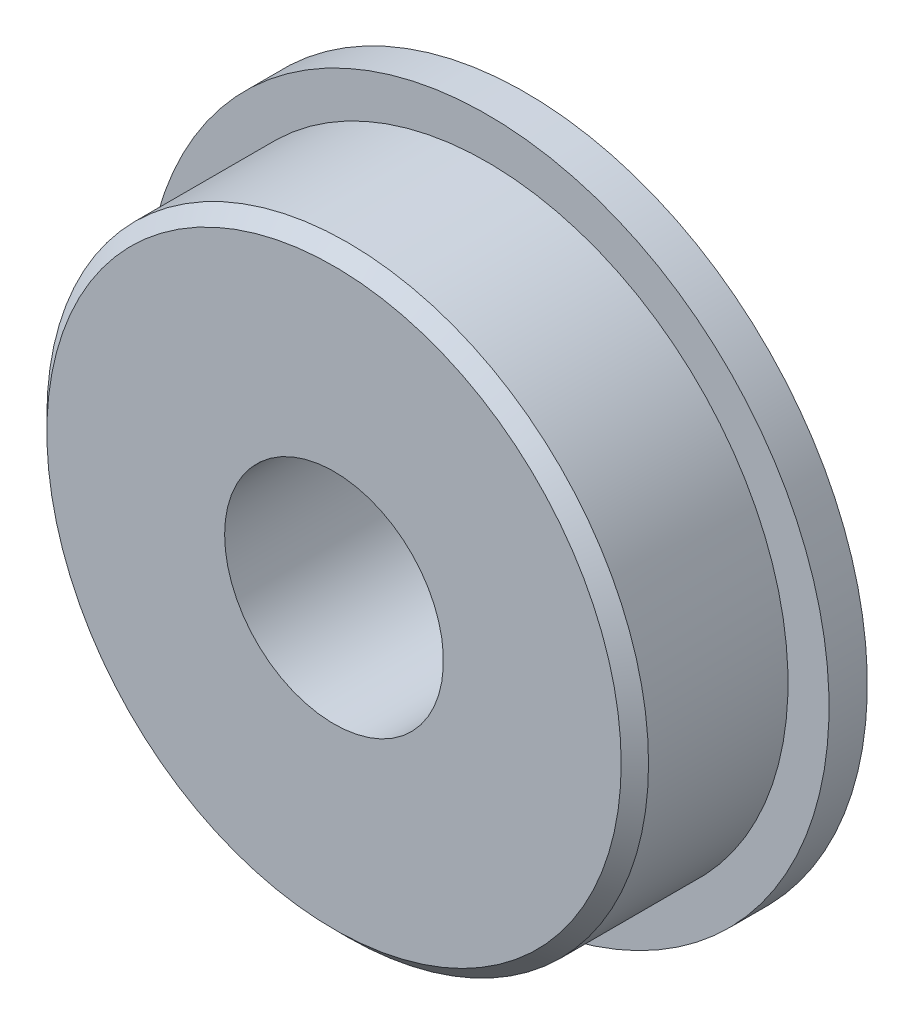
SolidWorks part; units mm, degrees
ref_plane "Front Plane" through (0, 0, 0) normal (0, 0, 1) x (1, 0, 0)
ref_plane "Top Plane" through (0, 0, 0) normal (0, 1, 0) x (1, 0, 0)
ref_plane "Right Plane" through (0, 0, 0) normal (1, 0, 0) x (0, 0, -1)
sketch "Sketch1" plane through (0, 0, 0) normal (0, 1, 0) x (1, 0, 0)
  line L0 (0, 20.1786) -> (0, -22.4643) construction
  line L1 (-16.9286, 0) -> (20.5, 0) construction
  line L2 (-12.5, 0) -> (-12.5, -1.4)
  line L3 (-12.5, -1.4) -> (-11, -1.4)
  line L4 (-11, -1.4) -> (-11, -7)
  line L5 (-11, -7) -> (-4, -7)
  line L6 (-4, -7) -> (-4, 0)
  line L7 (-4, 0) -> (-12.5, 0)
  dimension "D1" = 11
  dimension "D2" = 4
  dimension "D3" = 7
  dimension "D4" = 1.5
  dimension "D5" = 1.4
revolve "Revolve1" add sketch "Sketch1" angle 360 about L0
chamfer "Chamfer1" distance 0.5 angle 45 1 edges at (-11, 0, 7)
